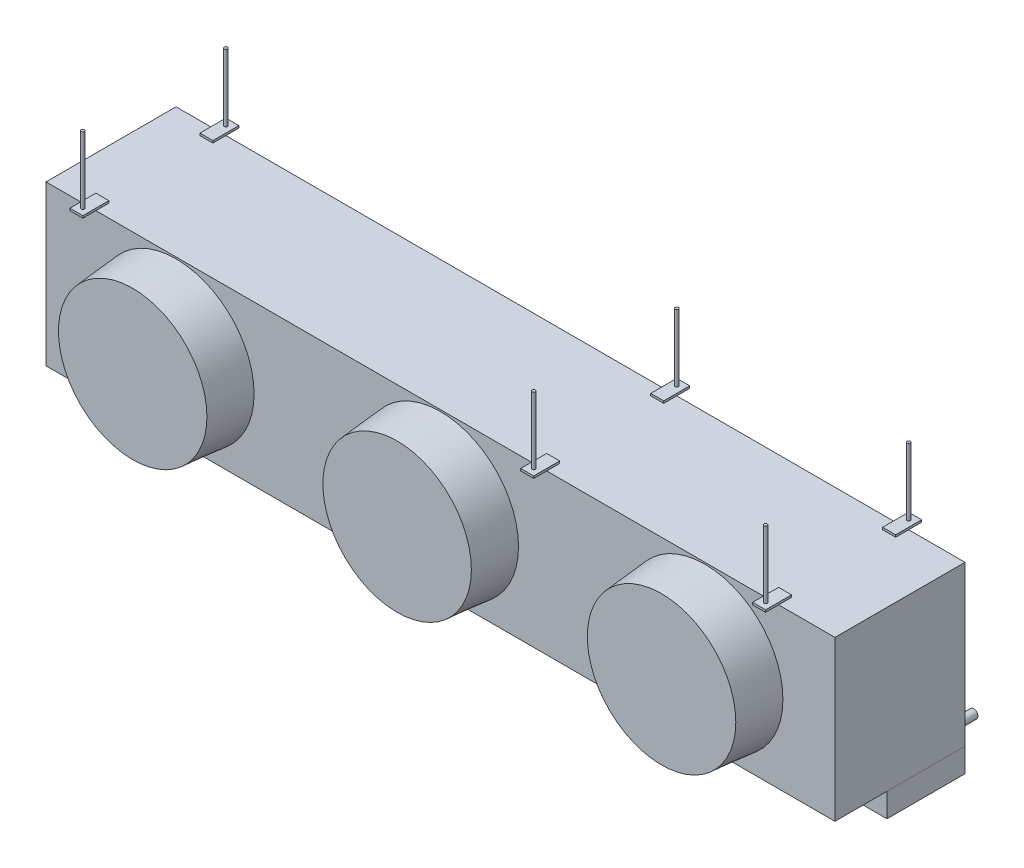
SolidWorks part; units mm, degrees
ref_plane "Front" through (0, 0, 0) normal (0, 0, 1) x (1, 0, 0)
ref_plane "Top" through (0, 0, 0) normal (0, 1, 0) x (1, 0, 0)
ref_plane "Right" through (0, 0, 0) normal (1, 0, 0) x (0, 0, -1)
sketch "Sketch1" plane through (0, 0, 0) normal (0, 1, 0) x (1, 0, 0)
  line L1 (-1155.7, 190.5) -> (1155.7, 190.5)
  line L2 (-1155.7, 190.5) -> (-1155.7, -190.5)
  line L3 (-1155.7, -190.5) -> (1155.7, -190.5)
  line L4 (1155.7, 190.5) -> (1155.7, -190.5)
  line L5 (-1155.7, 190.5) -> (1155.7, -190.5) construction
  line L6 (-1155.7, -190.5) -> (1155.7, 190.5) construction
  point P0 (0, 0)
  dimension "D1" = 2311.4
  dimension "D2" = 381
extrude "Boss-Extrude1" add sketch "Sketch1" along normal blind 466.725
sketch "Sketch2" plane through (0, 0, 190.5) normal (0, 0, 1) x (1, 0, 0)
  line L0 (0, 0) -> (0, 466.725) construction
  line L1 (-1155.7, 466.725) -> (1155.7, 466.725) construction
  line L2 (0, 233.3625) -> (-1155.7, 233.3625) construction
  line L3 (-1155.7, 466.725) -> (-1155.7, 0) construction
  line L4 (0, 233.3625) -> (1155.7, 233.3625) construction
  line L5 (1155.7, 466.725) -> (1155.7, 0) construction
  circle A0 centre (0, 233.3625) radius 228.6
  circle A1 centre (774.7, 233.3625) radius 228.6
  circle A2 centre (-774.7, 233.3625) radius 228.6
  dimension "D1" = 457.2
  dimension "D3" = 381
  dimension "D2" = 381
extrude "Boss-Extrude2" add sketch "Sketch2" along normal blind 127 draft 5
sketch "Sketch3" plane through (0, 466.725, 0) normal (0, 1, 0) x (1, 0, 0)
  line L0 (1155.7, 190.5) -> (-1155.7, 190.5) construction
  line L1 (273.05, 228.6) -> (311.15, 228.6)
  line L2 (273.05, 228.6) -> (273.05, 152.4)
  line L3 (273.05, 152.4) -> (311.15, 152.4)
  line L4 (311.15, 228.6) -> (311.15, 152.4)
  line L5 (273.05, 228.6) -> (311.15, 152.4) construction
  line L6 (273.05, 152.4) -> (311.15, 228.6) construction
  line L7 (1155.7, -190.5) -> (1155.7, 190.5) construction
  line L8 (273.05, -152.4) -> (311.15, -152.4)
  line L9 (273.05, -152.4) -> (273.05, -228.6)
  line L10 (273.05, -228.6) -> (311.15, -228.6)
  line L11 (311.15, -152.4) -> (311.15, -228.6)
  line L12 (273.05, -152.4) -> (311.15, -228.6) construction
  line L13 (273.05, -228.6) -> (311.15, -152.4) construction
  line L14 (546.1, -190.5) -> (1003.3, -190.5) construction
  line L15 (952.5, 228.6) -> (990.6, 228.6)
  line L16 (952.5, 228.6) -> (952.5, 152.4)
  line L17 (952.5, 152.4) -> (990.6, 152.4)
  line L18 (990.6, 228.6) -> (990.6, 152.4)
  line L19 (952.5, 228.6) -> (990.6, 152.4) construction
  line L20 (952.5, 152.4) -> (990.6, 228.6) construction
  line L21 (952.5, -152.4) -> (990.6, -152.4)
  line L22 (952.5, -152.4) -> (952.5, -228.6)
  line L23 (952.5, -228.6) -> (990.6, -228.6)
  line L24 (990.6, -152.4) -> (990.6, -228.6)
  line L25 (952.5, -152.4) -> (990.6, -228.6) construction
  line L26 (952.5, -228.6) -> (990.6, -152.4) construction
  line L27 (-1003.3, -190.5) -> (-546.1, -190.5) construction
  line L28 (-1047.75, 228.6) -> (-1009.65, 228.6)
  line L29 (-1047.75, 228.6) -> (-1047.75, 152.4)
  line L30 (-1047.75, 152.4) -> (-1009.65, 152.4)
  line L31 (-1009.65, 228.6) -> (-1009.65, 152.4)
  line L32 (-1047.75, 228.6) -> (-1009.65, 152.4) construction
  line L33 (-1047.75, 152.4) -> (-1009.65, 228.6) construction
  line L34 (-1047.75, -152.4) -> (-1009.65, -152.4)
  line L35 (-1047.75, -152.4) -> (-1047.75, -228.6)
  line L36 (-1047.75, -228.6) -> (-1009.65, -228.6)
  line L37 (-1009.65, -152.4) -> (-1009.65, -228.6)
  line L38 (-1047.75, -152.4) -> (-1009.65, -228.6) construction
  line L39 (-1047.75, -228.6) -> (-1009.65, -152.4) construction
  line L40 (-1028.7, -190.5) -> (-1028.7, 190.5) construction
  line L41 (971.55, 190.5) -> (971.55, -190.5) construction
  line L42 (-1028.7, 190.5) -> (0, 190.5) construction
  line L43 (0, 190.5) -> (971.55, 190.5) construction
  line L44 (0, 190.5) -> (971.55, 190.5) construction
  line L45 (-1028.7, 228.6) -> (-1028.7, 209.55) construction
  line L46 (-1028.7, -228.6) -> (-1028.7, -209.55) construction
  line L47 (292.1, 209.55) -> (292.1, 190.5) construction
  line L48 (292.1, -209.55) -> (292.1, -228.6) construction
  line L49 (971.55, 190.5) -> (971.55, 209.55) construction
  line L50 (971.55, -190.5) -> (971.55, -209.55) construction
  line L51 (-1155.7, 0) -> (-1028.7, 0) construction
  line L53 (-1155.7, 190.5) -> (-1155.7, -190.5) construction
  line L54 (-1155.7, -190.5) -> (1155.7, -190.5) construction
  circle A0 centre (-1028.7, 209.55) radius 4.7625
  circle A1 centre (-1028.7, -209.55) radius 4.7625
  circle A2 centre (971.55, 209.55) radius 4.7625
  circle A3 centre (971.55, -209.55) radius 4.7625
  circle A4 centre (292.1, -209.55) radius 4.7625
  circle A5 centre (292.1, 209.55) radius 4.7625
  point P0 (292.1, 190.5)
  point P7 (292.1, -190.5)
  point P14 (971.55, 190.5)
  point P19 (971.55, -190.5)
  point P26 (-1028.7, 190.5)
  point P31 (-1028.7, -190.5)
  dimension "D2" = 9.525
  dimension "D5" = 419.1
  dimension "D1" = 127
  dimension "D3" = 19.05
  dimension "D4" = 38.1
  dimension "D6" = 2000.25
  dimension "D7" = 679.45
  dimension "D8" = 184.15
extrude "Boss-Extrude3" add sketch "Sketch3" along normal blind 6.35
sketch "Sketch4" plane through (0, 466.725, 0) normal (0, 1, 0) x (1, 0, 0)
  circle A0 centre (-1028.7, 209.55) radius 4.7625 construction
  circle A1 centre (-1028.7, 209.55) radius 4.7625
  circle A2 centre (-1028.7, -209.55) radius 4.7625 construction
  circle A3 centre (-1028.7, -209.55) radius 4.7625
  circle A4 centre (292.1, -209.55) radius 4.7625 construction
  circle A5 centre (292.1, -209.55) radius 4.7625
  circle A6 centre (292.1, 209.55) radius 4.7625 construction
  circle A7 centre (292.1, 209.55) radius 4.7625
  circle A8 centre (971.55, 209.55) radius 4.7625 construction
  circle A9 centre (971.55, 209.55) radius 4.7625
  circle A10 centre (971.55, -209.55) radius 4.7625 construction
  circle A11 centre (971.55, -209.55) radius 4.7625
extrude "Boss-Extrude4" add sketch "Sketch4" along normal blind 203.2 separate body
sketch "Sketch5" plane through (0, 0, 0) normal (0, -1, 0) x (1, 0, 0)
  line L0 (0, 0) -> (0, -76.2) construction
  line L2 (-1155.7, 38.1) -> (1155.7, 38.1)
  line L3 (-1155.7, 38.1) -> (-1155.7, -190.5)
  line L4 (-1155.7, -190.5) -> (1155.7, -190.5)
  line L5 (1155.7, 38.1) -> (1155.7, -190.5)
  line L6 (-1155.7, 38.1) -> (1155.7, -190.5) construction
  line L7 (-1155.7, -190.5) -> (1155.7, 38.1) construction
  dimension "D1" = 228.6
extrude "Boss-Extrude5" add sketch "Sketch5" along normal blind 69.85 separate body
sketch "Sketch6" plane through (0, -69.85, 0) normal (0, -1, 0) x (1, 0, 0)
  line L0 (0, 38.1) -> (0, -190.5) construction
  line L1 (1155.7, 38.1) -> (-1155.7, 38.1) construction
  line L2 (-1155.7, -190.5) -> (1155.7, -190.5) construction
  circle A0 centre (0, -76.2) radius 12.7
  circle A1 centre (0, -76.2) radius 11.1125
  dimension "D1" = 25.4
  dimension "D2" = 22.225
extrude "Boss-Extrude6" add sketch "Sketch6" along normal blind 44.45
sketch "Sketch7" plane through (0, 0, -190.5) normal (0, 0, -1) x (-1, 0, 0)
  line L0 (0, 0) -> (0, 19.05) construction
  line L1 (0, 19.05) -> (-1104.9, 19.05) construction
  line L2 (0, 19.05) -> (1104.9, 19.05) construction
  line L3 (-1155.7, 466.725) -> (-1155.7, 0) construction
  line L4 (-1155.7, 0) -> (1155.7, 0) construction
  circle A0 centre (-1104.9, 19.05) radius 12.7
  circle A1 centre (1104.9, 19.05) radius 12.7
  dimension "D1" = 25.4
  dimension "D2" = 50.8
  dimension "D3" = 19.05
extrude "Boss-Extrude7" add sketch "Sketch7" along normal blind 76.2
sketch "Sketch8" plane through (0, 466.725, 0) normal (0, 1, 0) x (1, 0, 0)
  line L0 (971.7815, 209.1167) -> (243.0564, 209.1167) construction
  line L1 (242.404, 209.7447) -> (-1028.4714, 209.7447) construction
  dimension "D1" = 728.7251
  dimension "D2" = 1270.8754
  dimension "D3" = 2000.2529
